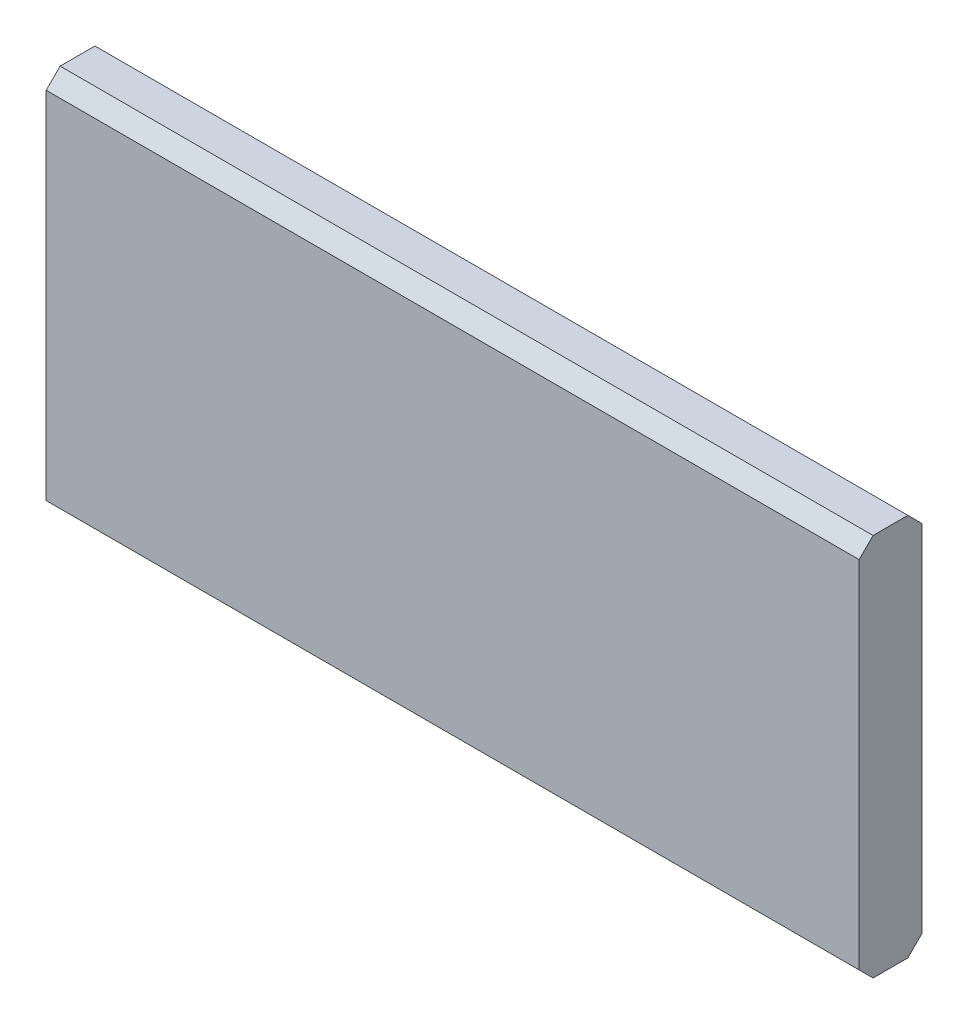
SolidWorks part; units mm, degrees
ref_plane "Plan de face" through (0, 0, 0) normal (0, 0, 1) x (1, 0, 0)
ref_plane "Plan de dessus" through (0, 0, 0) normal (0, 1, 0) x (1, 0, 0)
ref_plane "Plan de droite" through (0, 0, 0) normal (1, 0, 0) x (0, 0, -1)
sketch "Esquisse1" plane through (0, 0, 0) normal (0, 0, 1) x (1, 0, 0)
  line L1 (0, 0) -> (350, 0)
  line L2 (0, 0) -> (0, 165)
  line L3 (0, 165) -> (350, 165)
  line L4 (350, 0) -> (350, 165)
  dimension "D1" = 165
  dimension "D2" = 350
extrude "Boss.-Extru.1" add sketch "Esquisse1" along normal blind 27
chamfer "Chanfrein1" distance 6 angle 45 4 edges at (175, 0, 27) (175, 165, 27) (175, 0, 0) (175, 165, 0)
